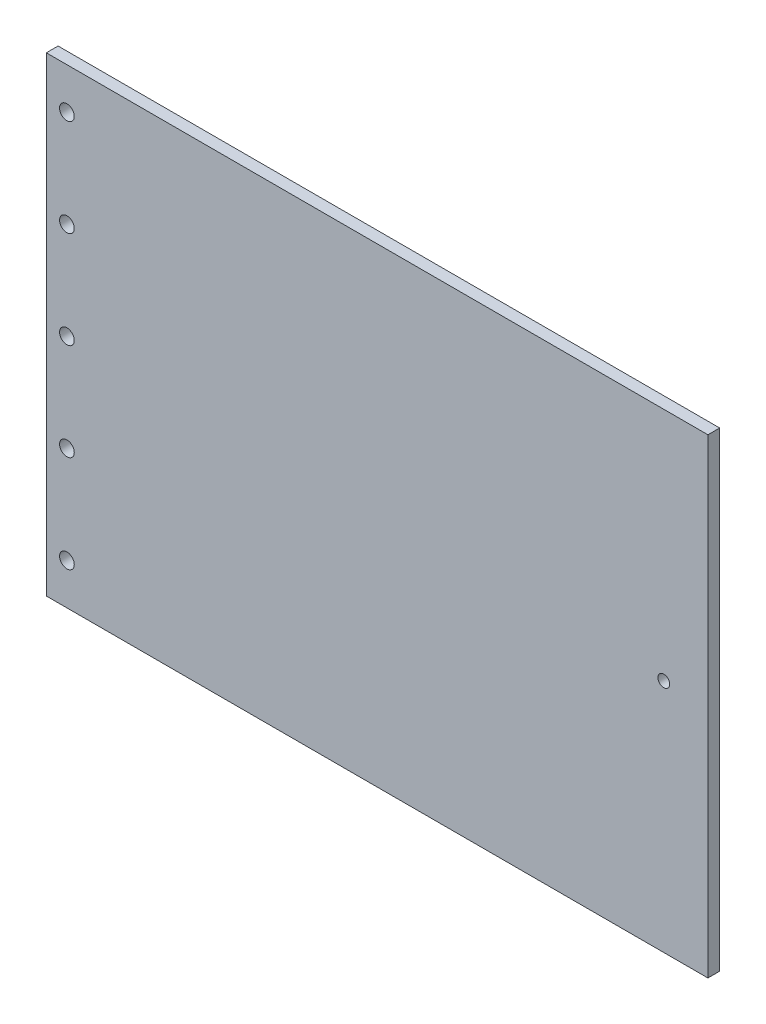
SolidWorks part; units mm, degrees
material "Сталь 3 ГОСТ 535-88"
ref_plane "Спереди" through (0, 0, 0) normal (0, 0, 1) x (1, 0, 0)
ref_plane "Сверху" through (0, 0, 0) normal (0, 1, 0) x (1, 0, 0)
ref_plane "Справа" through (0, 0, 0) normal (1, 0, 0) x (0, 0, -1)
sketch "Эскиз1" plane through (0, 0, 0) normal (0, 0, 1) x (1, 0, 0)
  line L0 (7, 80) -> (0, 80) construction
  line L1 (0, 0) -> (225, 0)
  line L2 (0, 0) -> (0, 160)
  line L3 (0, 160) -> (225, 160)
  line L4 (225, 0) -> (225, 160)
  line L5 (7, 80) -> (7, 0) construction
  line L6 (7, 80) -> (7, 160) construction
  circle A0 centre (7, 80) radius 2.5
  circle A1 centre (7, 47) radius 2.5
  circle A2 centre (7, 14) radius 2.5
  circle A3 centre (7, 113) radius 2.5
  circle A4 centre (7, 146) radius 2.5
  dimension "D3" = 5
  dimension "D4" = 7
  dimension "D5" = 33
  dimension "D6" = 33
  dimension "D7" = 33
  dimension "D8" = 33
  dimension "D1" = 225
  dimension "D2" = 160
extrude "Бобышка-Вытянуть1" add sketch "Эскиз1" along normal blind 4
sketch "Эскиз2" plane through (0, 0, 4) normal (0, 0, 1) x (1, 0, 0)
  line L0 (225, 80) -> (210, 80) construction
  line L1 (225, 0) -> (225, 160) construction
  circle A0 centre (210, 80) radius 2
  point P5 (225, 80)
  dimension "D1" = 4
  dimension "D2" = 15
extrude "Вырез-Вытянуть1" cut sketch "Эскиз2" against normal through all
